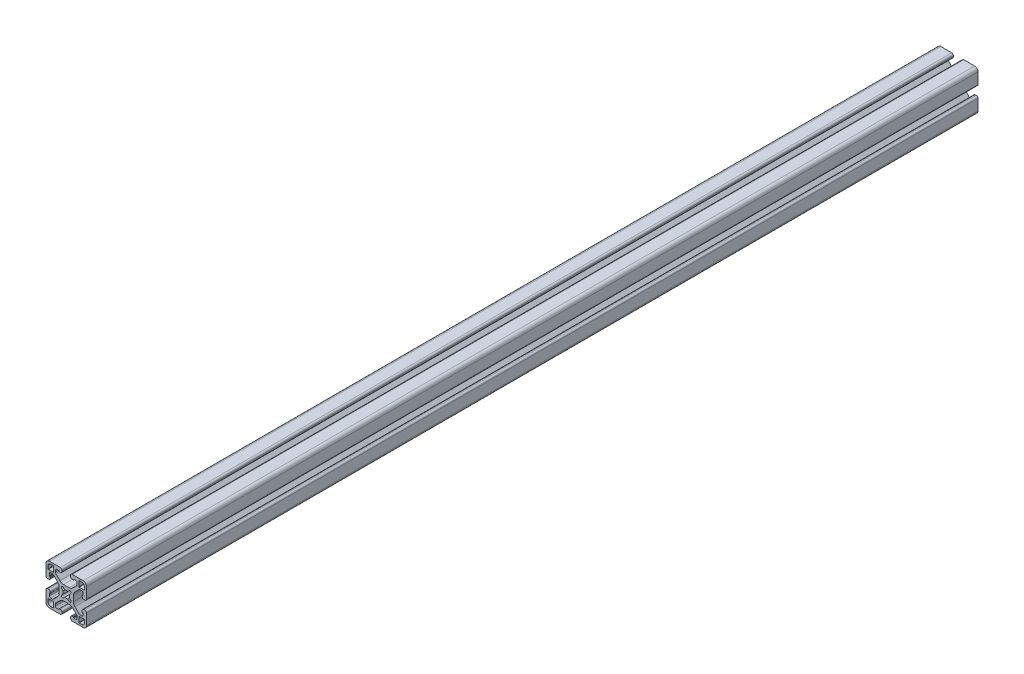
SolidWorks part; units mm, degrees
ref_plane "Front Plane" through (0, 0, 0) normal (0, 0, 1) x (1, 0, 0)
ref_plane "Top Plane" through (0, 0, 0) normal (0, 1, 0) x (1, 0, 0)
ref_plane "Right Plane" through (0, 0, 0) normal (1, 0, 0) x (0, 0, -1)
sketch "Sketch1" plane through (0, 0, 0) normal (0, 0, 1) x (1, 0, 0)
  line L0 (-66.7042, -2.4885) -> (-65.3338, -1.1181)
  line L1 (-65.3338, 1.5948) -> (-66.7042, 2.9652)
  line L2 (-65.0878, 4.5817) -> (-63.7174, 3.2113)
  line L3 (-61.0045, 3.2113) -> (-59.7212, 4.484)
  line L4 (-58.1153, 2.8781) -> (-59.3881, 1.5948)
  line L5 (-59.3881, -1.1181) -> (-58.0176, -2.4885)
  line L6 (-59.6341, -4.1049) -> (-61.0045, -2.7345)
  line L7 (-63.7174, -2.7345) -> (-65.0878, -4.1049)
  line L8 (-79.6075, 12.4812) -> (-79.6075, 14.691)
  line L9 (-76.8135, 17.485) -> (-74.6037, 17.485)
  line L10 (-74.2227, 17.104) -> (-74.2227, 12.4812)
  line L11 (-74.6037, 12.1002) -> (-79.2265, 12.1002)
  line L12 (-74.6037, -17.0082) -> (-76.8135, -17.0082)
  line L13 (-79.6075, -14.2142) -> (-79.6075, -12.0044)
  line L14 (-79.2265, -11.6234) -> (-74.6037, -11.6234)
  line L15 (-74.2227, -12.0044) -> (-74.2227, -16.6272)
  line L16 (-45.1143, -12.0044) -> (-45.1143, -14.2142)
  line L17 (-47.9083, -17.0082) -> (-50.1181, -17.0082)
  line L18 (-50.4991, -16.6272) -> (-50.4991, -12.0044)
  line L19 (-50.1181, -11.6234) -> (-45.4953, -11.6234)
  line L20 (-50.1181, 17.485) -> (-47.9083, 17.485)
  line L21 (-45.1143, 14.691) -> (-45.1143, 12.4812)
  line L22 (-45.4953, 12.1002) -> (-50.1181, 12.1002)
  line L23 (-50.4991, 12.4812) -> (-50.4991, 17.104)
  line L24 (-46.5368, -7.0006) -> (-46.5368, -8.7746)
  line L25 (-47.8067, -10.0486) -> (-49.3926, -10.0486)
  line L26 (-50.2907, -9.6767) -> (-54.2388, -5.7286)
  line L27 (-55.6299, -2.3699) -> (-55.6299, 2.8467)
  line L28 (-54.2388, 6.2053) -> (-50.2907, 10.1534)
  line L29 (-49.3926, 10.5254) -> (-47.8067, 10.5254)
  line L30 (-46.5368, 9.2513) -> (-46.5368, 7.4774)
  line L31 (-46.9178, 7.0964) -> (-46.994, 7.0964)
  line L32 (-47.375, 6.7154) -> (-47.3749, 5.8772)
  line L33 (-45.8001, 4.3024) -> (-44.8857, 4.3024)
  line L34 (-43.3109, 5.8772) -> (-43.3109, 16.1134)
  line L35 (-46.4859, 19.2884) -> (-56.7221, 19.2884)
  line L36 (-58.2969, 17.7136) -> (-58.2969, 16.7992)
  line L37 (-56.7222, 15.2244) -> (-55.884, 15.2244)
  line L38 (-55.503, 15.6054) -> (-55.503, 15.6816)
  line L39 (-55.122, 16.0626) -> (-53.348, 16.0626)
  line L40 (-52.0739, 14.7926) -> (-52.0739, 13.2067)
  line L41 (-52.4459, 12.3087) -> (-56.394, 8.3606)
  line L42 (-59.7526, 6.9694) -> (-64.9693, 6.9694)
  line L43 (-68.3279, 8.3606) -> (-72.276, 12.3087)
  line L44 (-72.6479, 13.2067) -> (-72.6479, 14.7926)
  line L45 (-71.3739, 16.0626) -> (-69.5999, 16.0626)
  line L46 (-69.2189, 15.6816) -> (-69.2189, 15.6054)
  line L47 (-68.8379, 15.2244) -> (-67.9997, 15.2244)
  line L48 (-66.4249, 16.7992) -> (-66.4249, 17.7136)
  line L49 (-67.9997, 19.2884) -> (-78.2359, 19.2884)
  line L50 (-81.4109, 16.1134) -> (-81.4109, 5.8772)
  line L51 (-79.8361, 4.3024) -> (-78.9217, 4.3024)
  line L52 (-77.3469, 5.8772) -> (-77.3469, 6.7154)
  line L53 (-77.7279, 7.0964) -> (-77.8041, 7.0964)
  line L54 (-78.1851, 7.4774) -> (-78.1851, 9.2513)
  line L55 (-76.9151, 10.5254) -> (-75.3293, 10.5254)
  line L56 (-74.4312, 10.1534) -> (-70.4831, 6.2053)
  line L57 (-69.0919, 2.8467) -> (-69.0919, -2.3699)
  line L58 (-70.4831, -5.7286) -> (-74.4312, -9.6767)
  line L59 (-75.3293, -10.0486) -> (-76.9151, -10.0486)
  line L60 (-78.1851, -8.7746) -> (-78.1851, -7.0006)
  line L61 (-77.8041, -6.6196) -> (-77.7279, -6.6196)
  line L62 (-77.3469, -6.2386) -> (-77.3469, -5.4004)
  line L63 (-78.9217, -3.8256) -> (-79.8361, -3.8256)
  line L64 (-81.4109, -5.4004) -> (-81.4109, -15.6366)
  line L65 (-78.2359, -18.8116) -> (-67.9997, -18.8116)
  line L66 (-66.4249, -17.2368) -> (-66.4249, -16.3224)
  line L67 (-67.9997, -14.7476) -> (-68.8379, -14.7476)
  line L68 (-69.2189, -15.1286) -> (-69.2189, -15.2048)
  line L69 (-69.5999, -15.5858) -> (-71.3739, -15.5858)
  line L70 (-72.6479, -14.3158) -> (-72.6479, -12.7299)
  line L71 (-72.276, -11.8319) -> (-68.3279, -7.8838)
  line L72 (-64.9693, -6.4926) -> (-59.7526, -6.4926)
  line L73 (-56.394, -7.8838) -> (-52.4459, -11.8319)
  line L74 (-52.0739, -12.7299) -> (-52.0739, -14.3158)
  line L75 (-53.348, -15.5858) -> (-55.122, -15.5858)
  line L76 (-55.503, -15.2048) -> (-55.503, -15.1286)
  line L77 (-55.884, -14.7476) -> (-56.7222, -14.7476)
  line L78 (-58.2969, -16.3224) -> (-58.2969, -17.2368)
  line L79 (-56.7221, -18.8116) -> (-46.4859, -18.8116)
  line L80 (-43.3109, -15.6366) -> (-43.3109, -5.4004)
  line L81 (-44.8857, -3.8256) -> (-45.8001, -3.8256)
  line L82 (-47.3749, -5.4004) -> (-47.375, -6.2386)
  line L83 (-46.994, -6.6196) -> (-46.9178, -6.6196)
  arc A0 (-66.7042, -2.4885) -> (-65.0878, -4.1049) centre (-65.896, -3.2967) ccw
  arc A1 (-65.3338, 1.5948) -> (-65.3338, -1.1181) centre (-62.3609, 0.2384) ccw
  arc A2 (-65.0878, 4.5817) -> (-66.7042, 2.9652) centre (-65.896, 3.7734) ccw
  arc A3 (-61.0045, 3.2113) -> (-63.7174, 3.2113) centre (-62.3609, 0.2384) ccw
  arc A4 (-58.1153, 2.8781) -> (-59.7212, 4.484) centre (-58.8259, 3.7734) ccw
  arc A5 (-59.3881, -1.1181) -> (-59.3881, 1.5948) centre (-62.3609, 0.2384) ccw
  arc A6 (-59.6341, -4.1049) -> (-58.0176, -2.4885) centre (-58.8259, -3.2967) ccw
  arc A7 (-63.7174, -2.7345) -> (-61.0045, -2.7345) centre (-62.3609, 0.2384) ccw
  arc A8 (-79.6075, 12.4812) -> (-79.2265, 12.1002) centre (-79.2265, 12.4812) ccw
  arc A9 (-76.8135, 17.485) -> (-79.6075, 14.691) centre (-76.8135, 14.691) ccw
  arc A10 (-74.2227, 17.104) -> (-74.6037, 17.485) centre (-74.6037, 17.104) ccw
  arc A11 (-74.6037, 12.1002) -> (-74.2227, 12.4812) centre (-74.6037, 12.4812) ccw
  arc A12 (-74.6037, -17.0082) -> (-74.2227, -16.6272) centre (-74.6037, -16.6272) ccw
  arc A13 (-79.6075, -14.2142) -> (-76.8135, -17.0082) centre (-76.8135, -14.2142) ccw
  arc A14 (-79.2265, -11.6234) -> (-79.6075, -12.0044) centre (-79.2265, -12.0044) ccw
  arc A15 (-74.2227, -12.0044) -> (-74.6037, -11.6234) centre (-74.6037, -12.0044) ccw
  arc A16 (-45.1143, -12.0044) -> (-45.4953, -11.6234) centre (-45.4953, -12.0044) ccw
  arc A17 (-47.9083, -17.0082) -> (-45.1143, -14.2142) centre (-47.9083, -14.2142) ccw
  arc A18 (-50.4991, -16.6272) -> (-50.1181, -17.0082) centre (-50.1181, -16.6272) ccw
  arc A19 (-50.1181, -11.6234) -> (-50.4991, -12.0044) centre (-50.1181, -12.0044) ccw
  arc A20 (-50.1181, 17.485) -> (-50.4991, 17.104) centre (-50.1181, 17.104) ccw
  arc A21 (-45.1143, 14.691) -> (-47.9083, 17.485) centre (-47.9083, 14.691) ccw
  arc A22 (-45.4953, 12.1002) -> (-45.1143, 12.4812) centre (-45.4953, 12.4812) ccw
  arc A23 (-50.4991, 12.4812) -> (-50.1181, 12.1002) centre (-50.1181, 12.4812) ccw
  arc A24 (-47.8067, -10.0486) -> (-46.5368, -8.7746) centre (-47.8067, -8.7786) ccw
  arc A25 (-50.2907, -9.6767) -> (-49.3926, -10.0486) centre (-49.3926, -8.7786) ccw
  arc A26 (-55.6299, -2.3699) -> (-54.2388, -5.7286) centre (-50.8801, -2.3699) ccw
  arc A27 (-54.2388, 6.2053) -> (-55.6299, 2.8467) centre (-50.8801, 2.8467) ccw
  arc A28 (-49.3926, 10.5254) -> (-50.2907, 10.1534) centre (-49.3926, 9.2554) ccw
  arc A29 (-46.5368, 9.2513) -> (-47.8067, 10.5254) centre (-47.8067, 9.2554) ccw
  arc A30 (-46.9178, 7.0964) -> (-46.5368, 7.4774) centre (-46.9178, 7.4774) ccw
  arc A31 (-46.994, 7.0964) -> (-47.375, 6.7154) centre (-46.994, 6.7154) ccw
  arc A32 (-47.3749, 5.8772) -> (-45.8001, 4.3024) centre (-45.8001, 5.8772) ccw
  arc A33 (-44.8857, 4.3024) -> (-43.3109, 5.8772) centre (-44.8857, 5.8772) ccw
  arc A34 (-43.3109, 16.1134) -> (-46.4859, 19.2884) centre (-46.4859, 16.1134) ccw
  arc A35 (-56.7221, 19.2884) -> (-58.2969, 17.7136) centre (-56.7221, 17.7136) ccw
  arc A36 (-58.2969, 16.7992) -> (-56.7222, 15.2244) centre (-56.7221, 16.7992) ccw
  arc A37 (-55.884, 15.2244) -> (-55.503, 15.6054) centre (-55.884, 15.6054) ccw
  arc A38 (-55.122, 16.0626) -> (-55.503, 15.6816) centre (-55.122, 15.6816) ccw
  arc A39 (-52.0739, 14.7926) -> (-53.348, 16.0626) centre (-53.3439, 14.7926) ccw
  arc A40 (-52.4459, 12.3087) -> (-52.0739, 13.2067) centre (-53.3439, 13.2067) ccw
  arc A41 (-59.7526, 6.9694) -> (-56.394, 8.3606) centre (-59.7526, 11.7192) ccw
  arc A42 (-68.3279, 8.3606) -> (-64.9693, 6.9694) centre (-64.9693, 11.7192) ccw
  arc A43 (-72.6479, 13.2067) -> (-72.276, 12.3087) centre (-71.3779, 13.2067) ccw
  arc A44 (-71.3739, 16.0626) -> (-72.6479, 14.7926) centre (-71.3779, 14.7926) ccw
  arc A45 (-69.2189, 15.6816) -> (-69.5999, 16.0626) centre (-69.5999, 15.6816) ccw
  arc A46 (-69.2189, 15.6054) -> (-68.8379, 15.2244) centre (-68.8379, 15.6054) ccw
  arc A47 (-67.9997, 15.2244) -> (-66.4249, 16.7992) centre (-67.9997, 16.7992) ccw
  arc A48 (-66.4249, 17.7136) -> (-67.9997, 19.2884) centre (-67.9997, 17.7136) ccw
  arc A49 (-78.2359, 19.2884) -> (-81.4109, 16.1134) centre (-78.2359, 16.1134) ccw
  arc A50 (-81.4109, 5.8772) -> (-79.8361, 4.3024) centre (-79.8361, 5.8772) ccw
  arc A51 (-78.9217, 4.3024) -> (-77.3469, 5.8772) centre (-78.9217, 5.8772) ccw
  arc A52 (-77.3469, 6.7154) -> (-77.7279, 7.0964) centre (-77.7279, 6.7154) ccw
  arc A53 (-78.1851, 7.4774) -> (-77.8041, 7.0964) centre (-77.8041, 7.4774) ccw
  arc A54 (-76.9151, 10.5254) -> (-78.1851, 9.2513) centre (-76.9151, 9.2554) ccw
  arc A55 (-74.4312, 10.1534) -> (-75.3293, 10.5254) centre (-75.3293, 9.2554) ccw
  arc A56 (-69.0919, 2.8467) -> (-70.4831, 6.2053) centre (-73.8417, 2.8467) ccw
  arc A57 (-70.4831, -5.7286) -> (-69.0919, -2.3699) centre (-73.8417, -2.3699) ccw
  arc A58 (-75.3293, -10.0486) -> (-74.4312, -9.6767) centre (-75.3293, -8.7786) ccw
  arc A59 (-78.1851, -8.7746) -> (-76.9151, -10.0486) centre (-76.9151, -8.7786) ccw
  arc A60 (-77.8041, -6.6196) -> (-78.1851, -7.0006) centre (-77.8041, -7.0006) ccw
  arc A61 (-77.7279, -6.6196) -> (-77.3469, -6.2386) centre (-77.7279, -6.2386) ccw
  arc A62 (-77.3469, -5.4004) -> (-78.9217, -3.8256) centre (-78.9217, -5.4004) ccw
  arc A63 (-79.8361, -3.8256) -> (-81.4109, -5.4004) centre (-79.8361, -5.4004) ccw
  arc A64 (-81.4109, -15.6366) -> (-78.2359, -18.8116) centre (-78.2359, -15.6366) ccw
  arc A65 (-67.9997, -18.8116) -> (-66.4249, -17.2368) centre (-67.9997, -17.2368) ccw
  arc A66 (-66.4249, -16.3224) -> (-67.9997, -14.7476) centre (-67.9997, -16.3224) ccw
  arc A67 (-68.8379, -14.7476) -> (-69.2189, -15.1286) centre (-68.8379, -15.1286) ccw
  arc A68 (-69.5999, -15.5858) -> (-69.2189, -15.2048) centre (-69.5999, -15.2048) ccw
  arc A69 (-72.6479, -14.3158) -> (-71.3739, -15.5858) centre (-71.3779, -14.3158) ccw
  arc A70 (-72.276, -11.8319) -> (-72.6479, -12.7299) centre (-71.3779, -12.7299) ccw
  arc A71 (-64.9693, -6.4926) -> (-68.3279, -7.8838) centre (-64.9693, -11.2424) ccw
  arc A72 (-56.394, -7.8838) -> (-59.7526, -6.4926) centre (-59.7526, -11.2424) ccw
  arc A73 (-52.0739, -12.7299) -> (-52.4459, -11.8319) centre (-53.3439, -12.7299) ccw
  arc A74 (-53.348, -15.5858) -> (-52.0739, -14.3158) centre (-53.3439, -14.3158) ccw
  arc A75 (-55.503, -15.2048) -> (-55.122, -15.5858) centre (-55.122, -15.2048) ccw
  arc A76 (-55.503, -15.1286) -> (-55.884, -14.7476) centre (-55.884, -15.1286) ccw
  arc A77 (-56.7222, -14.7476) -> (-58.2969, -16.3224) centre (-56.7221, -16.3224) ccw
  arc A78 (-58.2969, -17.2368) -> (-56.7221, -18.8116) centre (-56.7221, -17.2368) ccw
  arc A79 (-46.4859, -18.8116) -> (-43.3109, -15.6366) centre (-46.4859, -15.6366) ccw
  arc A80 (-43.3109, -5.4004) -> (-44.8857, -3.8256) centre (-44.8857, -5.4004) ccw
  arc A81 (-45.8001, -3.8256) -> (-47.3749, -5.4004) centre (-45.8001, -5.4004) ccw
  arc A82 (-47.375, -6.2386) -> (-46.994, -6.6196) centre (-46.994, -6.2386) ccw
  arc A83 (-46.5368, -7.0006) -> (-46.9178, -6.6196) centre (-46.9178, -7.0006) ccw
extrude "Extrude1" add sketch "Sketch1" against normal blind 838.2
